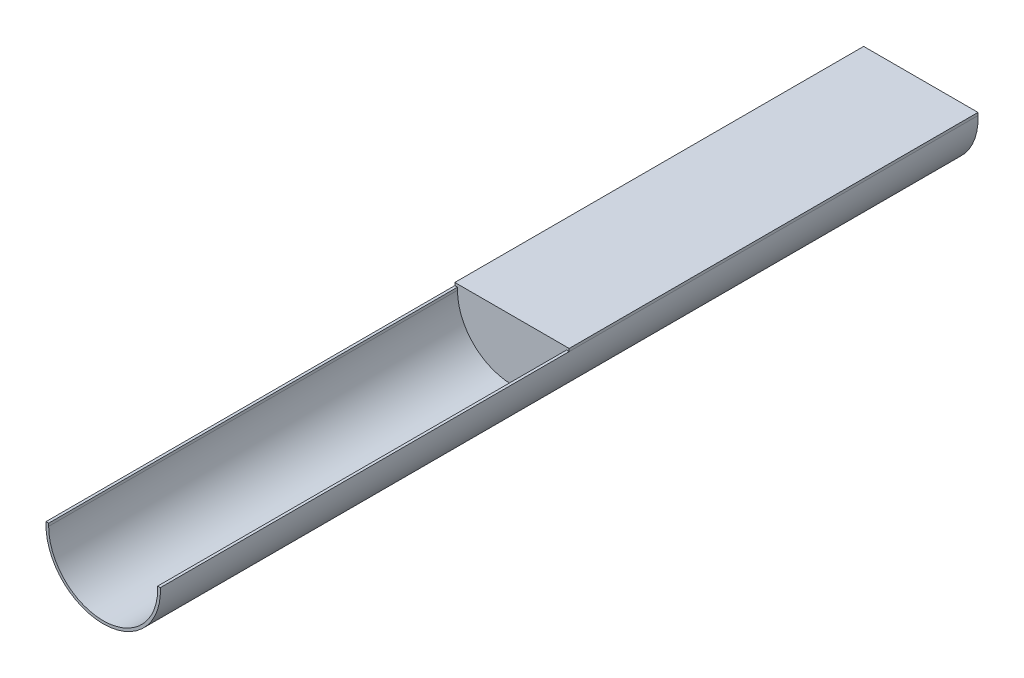
SolidWorks part; units mm, degrees
ref_plane "Front Plane" through (0, 0, 0) normal (0, 0, 1) x (1, 0, 0)
ref_plane "Top Plane" through (0, 0, 0) normal (0, 1, 0) x (1, 0, 0)
ref_plane "Right Plane" through (0, 0, 0) normal (1, 0, 0) x (0, 0, -1)
sketch "Sketch1" plane through (0, 0, 0) normal (0, 0, 1) x (1, 0, 0)
  line L1 (41.9524, 2) -> (40, 2)
  line L2 (40, 0) -> (40, 2)
  line L3 (-40, 0) -> (-40, 2)
  line L4 (-40, 2) -> (-41.9524, 2)
  line L5 (41.9524, 2) -> (-41.9524, 2) construction
  line L6 (40, 0) -> (-40, 0) construction
  arc A0 (-40, 0) -> (40, 0) centre (0, 0) ccw
  arc A1 (-41.9524, 2) -> (41.9524, 2) centre (0, 0) ccw
  dimension "D1" = 80
  dimension "D2" = 2
extrude "Boss-Extrude1" add sketch "Sketch1" along normal blind 600
sketch "Sketch2" plane through (0, 2, 0) normal (0, 1, 0) x (1, 0, 0)
  line L0 (41.9524, -600) -> (41.9524, 0) construction
  line L1 (-41.9524, 0) -> (41.9524, 0)
  line L2 (-41.9524, 0) -> (-41.9524, -300)
  line L3 (-41.9524, -300) -> (41.9524, -300)
  line L4 (41.9524, 0) -> (41.9524, -300)
  dimension "D1" = 300
extrude "Boss-Extrude2" add sketch "Sketch2" along normal blind 2
sketch "Sketch3" plane through (0, 0, 0) normal (0, 0, -1) x (-1, 0, 0)
  line L0 (41.9524, 2) -> (-41.9524, 2)
  arc A0 (-41.9524, 2) -> (41.9524, 2) centre (0, 0) ccw
extrude "Boss-Extrude3" add sketch "Sketch3" along normal blind 2 from offset 300
